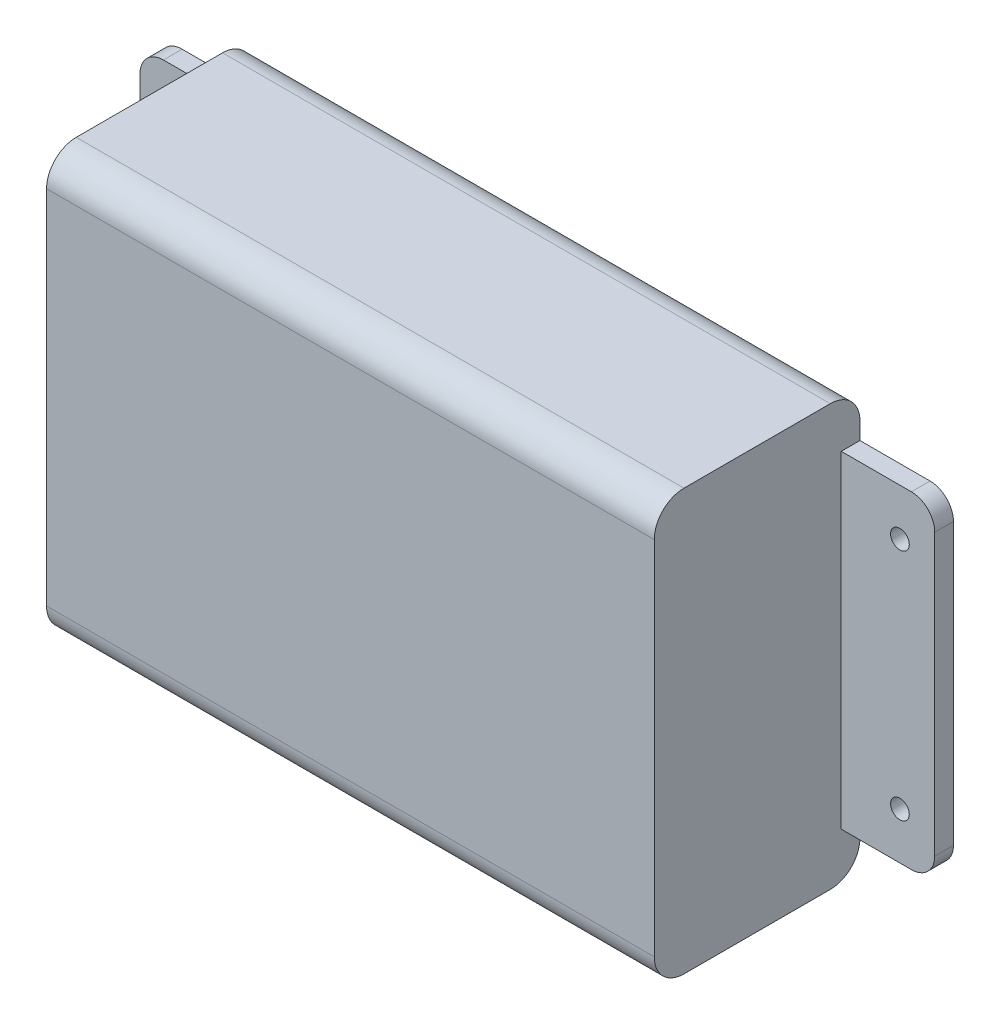
SolidWorks part; units mm, degrees
ref_plane "Front Plane" through (0, 0, 0) normal (0, 0, 1) x (1, 0, 0)
ref_plane "Top Plane" through (0, 0, 0) normal (0, 1, 0) x (1, 0, 0)
ref_plane "Right Plane" through (0, 0, 0) normal (1, 0, 0) x (0, 0, -1)
sketch "Sketch1" plane through (0, 0, 0) normal (0, 0, 1) x (1, 0, 0)
  line L1 (0, 0) -> (170, 0)
  line L2 (0, 0) -> (0, -90)
  line L3 (0, -90) -> (170, -90)
  line L4 (170, 0) -> (170, -90)
  dimension "D1" = 170
  dimension "D2" = 90
extrude "Boss-Extrude1" add sketch "Sketch1" along normal blind 44
fillet "Fillet1" radius 6.35 2 edges at (85, -90, 0) (85, 0, 0)
sketch "Sketch3" plane through (0, 0, 44) normal (0, 0, 1) x (1, 0, 0)
  line L10 (170, 0) -> (0, 0) construction
  line L11 (150, 0) -> (170, 0)
  line L12 (150, 0) -> (150, -90)
  line L13 (150, -90) -> (170, -90)
  line L14 (170, 0) -> (170, -90)
  line L15 (0, -90) -> (170, -90) construction
  line L16 (0, 0) -> (20, 0)
  line L17 (0, 0) -> (0, -90)
  line L18 (0, -90) -> (20, -90)
  line L19 (20, 0) -> (20, -90)
  dimension "D1" = 90
  dimension "D2" = 20
  dimension "D3" = 90
  dimension "D4" = 20
extrude "Cut-Extrude7" cut sketch "Sketch3" against normal blind 40
sketch "Sketch5" plane through (0, 0, 4) normal (0, 0, 1) x (1, 0, 0)
  line L0 (20, -89.5492) -> (20, -0.4508) construction
  line L1 (0, 0) -> (20, 0)
  line L2 (0, 0) -> (0, -10)
  line L3 (0, -10) -> (20, -10)
  line L4 (20, 0) -> (20, -10)
  line L5 (0, -0.4508) -> (0, -89.5492) construction
  line L6 (0, -80) -> (20, -80)
  line L7 (0, -80) -> (0, -90)
  line L8 (0, -90) -> (20, -90)
  line L9 (20, -80) -> (20, -90)
  line L10 (0, -90) -> (20, -90) construction
  line L11 (170, -89.5492) -> (170, -0.4508) construction
  line L12 (150, 0) -> (170, 0)
  line L13 (150, 0) -> (150, -10)
  line L14 (150, -10) -> (170, -10)
  line L15 (170, 0) -> (170, -10)
  line L16 (150, 0) -> (150, -90) construction
  line L17 (150, -80) -> (171.1019, -80)
  line L18 (150, -80) -> (150, -90)
  line L19 (150, -90) -> (171.1019, -90)
  line L20 (171.1019, -80) -> (171.1019, -90)
  dimension "D1" = 10
  dimension "D2" = 10
  dimension "D3" = 10
  dimension "D4" = 10
  dimension "D5" = 20
extrude "Cut-Extrude8" cut sketch "Sketch5" against normal blind 36
sketch "Sketch6" plane through (0, 0, 0) normal (0, 0, -1) x (-1, 0, 0)
  line L0 (0, -10) -> (-20, -10) construction
  line L1 (-20, -80) -> (0, -80) construction
  line L2 (-150, -10) -> (-170, -10) construction
  line L3 (-170, -80) -> (-150, -80) construction
  circle A0 centre (-162.5523, -20) radius 2
  circle A1 centre (-162.5523, -70) radius 2
  circle A2 centre (-10.5035, -20) radius 2
  circle A3 centre (-10.5035, -70) radius 2
  dimension "D1" = 4
  dimension "D2" = 4
  dimension "D3" = 4
  dimension "D4" = 4
  dimension "D5" = 10
  dimension "D6" = 10
  dimension "D7" = 50
  dimension "D8" = 10
  dimension "D9" = 10
  dimension "D10" = 50
extrude "Cut-Extrude9" cut sketch "Sketch6" against normal blind 36
fillet "Fillet3" radius 5 4 edges at (0, -10, 2) (0, -80, 2) (170, -80, 2) (170, -10, 2)
sketch "Sketch7" plane through (0, 0, 0) normal (0, 0, -1) x (-1, 0, 0)
  text T0 "ESC\r\n" font "Constantia" height in points 48
extrude "Cut-Extrude10" cut sketch "Sketch7" against normal blind 10
fillet "Fillet4" radius 6.35 2 edges at (85, -90, 44) (85, 0, 44)
